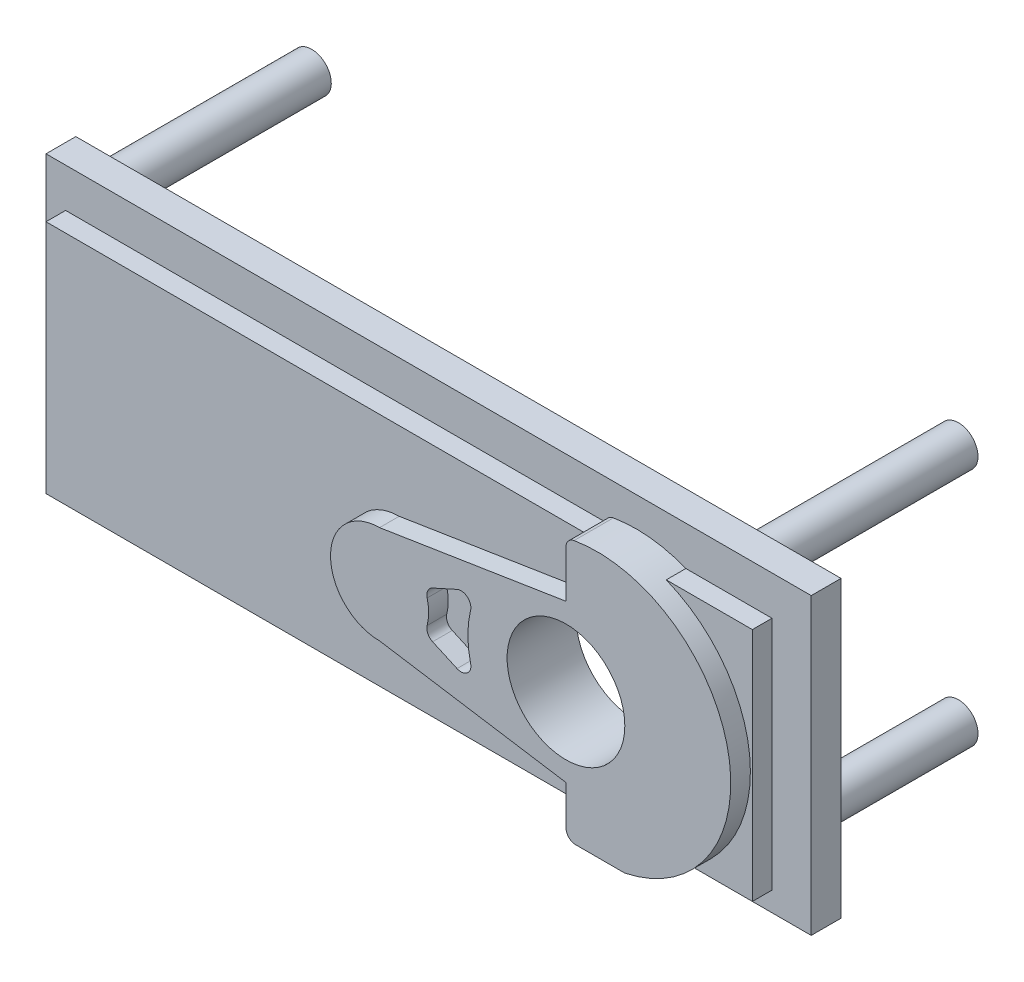
SolidWorks part; units mm, degrees
material "ABS PC"
ref_plane "Piano frontale" through (0, 0, 0) normal (0, 0, 1) x (1, 0, 0)
ref_plane "Piano superiore" through (0, 0, 0) normal (0, 1, 0) x (1, 0, 0)
ref_plane "Piano destro" through (0, 0, 0) normal (1, 0, 0) x (0, 0, -1)
sketch "Schizzo1" plane through (0, 0, 0) normal (0, 0, 1) x (1, 0, 0)
  line L1 (-19.5, -7.5) -> (19.5, -7.5)
  line L2 (-19.5, -7.5) -> (-19.5, 7.5)
  line L3 (-19.5, 7.5) -> (19.5, 7.5)
  line L4 (19.5, -7.5) -> (19.5, 7.5)
  line L5 (-19.5, -7.5) -> (19.5, 7.5) construction
  line L6 (-19.5, 7.5) -> (19.5, -7.5) construction
  point P0 (0, 0)
  dimension "D1" = 39
  dimension "D2" = 15
extrude "Estrusione-Estrusione1" add sketch "Schizzo1" along normal blind 2.52
sketch "Schizzo2" plane through (0, 0, 2.52) normal (0, 0, 1) x (1, 0, 0)
  line L0 (-19.5, 7.5) -> (-19.5, -7.5) construction
  line L1 (-18.5, -6.5) -> (17.5, -6.5)
  line L2 (-18.5, -6.5) -> (-18.5, 5.5)
  line L3 (-18.5, 5.5) -> (17.5, 5.5)
  line L4 (17.5, -6.5) -> (17.5, 5.5)
  line L5 (-18.5, -6.5) -> (17.5, 5.5) construction
  line L6 (-18.5, 5.5) -> (17.5, -6.5) construction
  line L8 (19.5, -7.5) -> (19.5, 7.5) construction
  line L9 (19.5, 7.5) -> (-19.5, 7.5) construction
  line L10 (-19.5, -7.5) -> (19.5, -7.5) construction
  line L15 (19.5, -7.5) -> (19.5, 7.5)
  line L16 (19.5, 7.5) -> (-19.5, 7.5)
  line L17 (-19.5, 7.5) -> (-19.5, -7.5)
  line L18 (-19.5, -7.5) -> (19.5, -7.5)
  line L19 (19.5, -7.5) -> (19.5, 7.5)
  line L20 (19.5, 7.5) -> (-19.5, 7.5)
  line L21 (-19.5, 7.5) -> (-19.5, -7.5)
  line L22 (-19.5, -7.5) -> (19.5, -7.5)
  point P0 (0, 0)
  dimension "D1" = 1
  dimension "D2" = 2
  dimension "D3" = 2
  dimension "D4" = 1
  dimension "D5" = 0
extrude "Taglio-Estrusione1" cut sketch "Schizzo2" against normal blind 1
sketch "Schizzo3" plane through (0, 0, 2.52) normal (0, 0, 1) x (1, 0, 0)
  line L0 (19.5, -7.5) -> (19.5, 7.5) construction
  line L1 (-19.5, -7.5) -> (19.5, -7.5) construction
  circle A0 centre (9, -1) radius 3
  dimension "D1" = 6
  dimension "D2" = 10.5
  dimension "D3" = 6.5
extrude "Taglio-Estrusione2" cut sketch "Schizzo3" against normal up to next
sketch "Schizzo4" plane through (0, 0, 2.52) normal (0, 0, 1) x (1, 0, 0)
  line L0 (9, -1) -> (-3, -1) construction
  line L1 (-0.5, 1.5) -> (9, 3)
  line L2 (-0.5, -3.5) -> (9, -5)
  line L3 (9, 3) -> (9, 5.3928)
  line L4 (9, -5) -> (9, -7)
  line L5 (-19.5, -7.5) -> (19.5, -7.5) construction
  line L6 (9.5, -7.5) -> (12, -7.5)
  line L7 (17.5, 5.5) -> (-18.5, 5.5) construction
  line L8 (17.5, -6.5) -> (17.5, 5.5) construction
  line L9 (3.4482, 0.7469) -> (2.2043, 0.1862)
  line L10 (2.2043, -2.1862) -> (3.4482, -2.7469)
  arc A0 (-0.5, 1.5) -> (-0.5, -3.5) centre (-0.5, -1) ccw
  circle A1 centre (9, -1) radius 3 construction
  arc A3 (12, -7.5) -> (9.4143, 5.8854) centre (10.5824, -0.8314) ccw
  arc A4 (9.4143, 5.8854) -> (9, 5.3928) centre (9.5, 5.3928) ccw
  arc A5 (9.5, -7.5) -> (9, -7) centre (9.5, -7) cw
  arc A6 (2.2043, 0.1862) -> (1.9248, -0.3914) centre (2.4097, -0.2697) ccw
  arc A7 (1.9248, -1.6086) -> (1.9248, -0.3914) centre (-0.5, -1) ccw
  circle A8 centre (9, -1) radius 5
  arc A9 (4.1397, 0.1737) -> (4.1397, -2.1737) centre (9, -1) ccw
  arc A10 (1.9248, -1.6086) -> (2.2043, -2.1862) centre (2.4097, -1.7303) ccw
  arc A11 (4.1397, 0.1737) -> (3.4482, 0.7469) centre (3.6537, 0.2911) ccw
  arc A12 (3.4482, -2.7469) -> (4.1397, -2.1737) centre (3.6537, -2.2911) ccw
  circle A13 centre (9, -1) radius 3
  point P19 (17.4, -0.8314)
  point P27 (9, 5.8)
  point P30 (9, -7.5)
  point P37 (1.7913, 0)
  point P40 (1.7913, -2)
  point P43 (4.5263, 1.2329)
  point P46 (4.5263, -3.2329)
  dimension "D2" = 5
  dimension "D3" = 4
  dimension "D8" = 0.5
  dimension "D9" = 0.5
  dimension "D14" = 0.5
  dimension "D15" = 0.5
  dimension "D16" = 0.5
  dimension "D17" = 0.5
  dimension "D1" = 12
  dimension "D4" = 4
  dimension "D5" = 3
  dimension "D6" = 0.3
  dimension "D7" = 0.1
  dimension "D11" = 3
  dimension "D12" = 3
  dimension "D13" = 4.4657
  dimension "D10" = 2
extrude "Estrusione-Estrusione2" add sketch "Schizzo4" along normal blind 2 from surface at -1 starting at face at (-0.5, -0.5, 1.52)
sketch "Schizzo5" plane through (0, 0, 0) normal (0, 0, -1) x (-1, 0, 0)
  line L8 (-18.5, 6.5) -> (-18.5, -6.5)
  line L9 (-18.5, -6.5) -> (18.5, -6.5)
  line L10 (18.5, -6.5) -> (18.5, 6.5)
  line L11 (18.5, 6.5) -> (-18.5, 6.5)
  line L12 (-18.5, 6.5) -> (-18.5, -6.5)
  line L13 (-18.5, -6.5) -> (18.5, -6.5)
  line L14 (18.5, -6.5) -> (18.5, 6.5)
  line L15 (18.5, 6.5) -> (-18.5, 6.5)
  dimension "D1" = 1
extrude "Taglio-Estrusione4" cut sketch "Schizzo5" against normal blind 1
sketch "Schizzo6" plane through (0, 0, 0) normal (0, 0, -1) x (-1, 0, 0)
  line L0 (-9, 4.9161) -> (-9, 4.1539)
  line L4 (-9, -6.1539) -> (-9, -6.9161)
  arc A7 (-9.8095, 3.1722) -> (-9.8095, -5.1722) centre (-9, -1) ccw
  arc A8 (-10.1667, 5.9021) -> (-10.1667, -7.9021) centre (-9, -1) ccw
  arc A9 (-9, 4.9161) -> (-10.1667, 5.9021) centre (-10, 4.9161) ccw
  arc A10 (-9, 4.1539) -> (-9.8095, 3.1722) centre (-10, 4.1539) cw
  arc A11 (-9, -6.1539) -> (-9.8095, -5.1722) centre (-10, -6.1539) ccw
  arc A12 (-9, -6.9161) -> (-10.1667, -7.9021) centre (-10, -6.9161) cw
  point P8 (-9, 6)
  point P15 (-9, -8)
  dimension "D2" = 14
  dimension "D3" = 1
  dimension "D4" = 1
  dimension "D5" = 1
  dimension "D1" = 8.5
  dimension "D6" = 1
extrude "Taglio-Estrusione9" cut sketch "Schizzo6" against normal blind 1.5
sketch "Schizzo11" plane through (0, 0, 0) normal (0, 0, -1) x (-1, 0, 0)
  line L0 (19.5, -7.5) -> (-9.1882, -7.5) construction
  line L5 (19.5, 7.5) -> (19.5, -7.5) construction
  line L6 (-19.5, 7.5) -> (19.5, 7.5) construction
  line L13 (-19.5, -7.5) -> (-19.5, 7.5) construction
  line L14 (-11.5981, -7.5) -> (-19.5, -7.5) construction
  circle A0 centre (-15.48, -5.8644) radius 1
  circle A1 centre (-15.48, 6.3644) radius 1
  circle A2 centre (17.48, 6.3644) radius 1
  circle A3 centre (17.48, -5.8644) radius 1
  dimension "D1" = 2
  dimension "D2" = 1.6356
  dimension "D3" = 2.02
  dimension "D4" = 1.1356
  dimension "D5" = 2.02
  dimension "D6" = 1.1356
  dimension "D7" = 4.02
  dimension "D8" = 1.6356
  dimension "D9" = 4.02
extrude "Estrusione-Estrusione3" add sketch "Schizzo11" along normal blind 11 from surface at -1 starting at face at (7.1674, -0.4068, 1)
sketch "Schizzo12" plane through (0, 0, 1) normal (0, 0, -1) x (-1, 0, 0)
  line L2 (19.5, -7.5) -> (-9.1882, -7.5) construction
  line L3 (-19.5, -7.5) -> (-19.5, 7.5) construction
  circle A0 centre (-0.2, -2) radius 1
  dimension "D1" = 2
  dimension "D2" = 5.5
  dimension "D3" = 19.3
extrude "Taglio-Estrusione10" cut sketch "Schizzo12" against normal blind 1.5
sketch "Schizzo13" plane through (0, 0, 1) normal (0, 0, -1) x (-1, 0, 0)
  circle A0 centre (-9, -1) radius 3
  circle A1 centre (-9, -1) radius 4.25
  circle A2 centre (-9, -1) radius 3 construction
  arc A3 (-9.8095, 3.1722) -> (-9.8095, -5.1722) centre (-9, -1) ccw construction
extrude "Estrusione-Estrusione4" add sketch "Schizzo13" along normal blind 1
